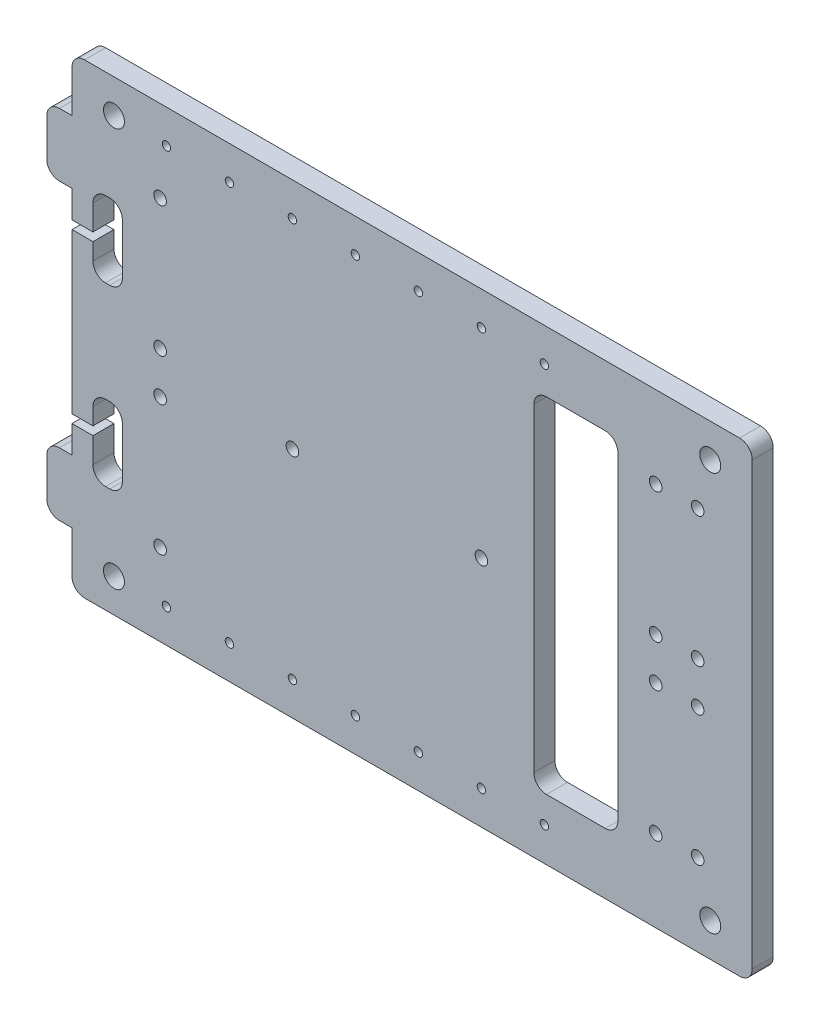
SolidWorks part; units mm, degrees
ref_plane "前视基准面" through (0, 0, 0) normal (0, 0, 1) x (1, 0, 0)
ref_plane "上视基准面" through (0, 0, 0) normal (0, 1, 0) x (1, 0, 0)
ref_plane "右视基准面" through (0, 0, 0) normal (1, 0, 0) x (0, 0, -1)
sketch "草图1" plane through (0, 0, 0) normal (0, 0, 1) x (1, 0, 0)
  line L1 (0, 0) -> (162, 0)
  line L2 (0, 0) -> (0, -111)
  line L3 (0, -111) -> (162, -111)
  line L4 (162, 0) -> (162, -111)
  dimension "D1" = 111
  dimension "D2" = 162
extrude "凸台-拉伸1" add sketch "草图1" along normal blind 5
sketch "草图2" plane through (0, 0, 0) normal (0, 0, -1) x (-1, 0, 0)
  line L8 (-130, -96.5) -> (-130, -14.5)
  line L9 (-130, -14.5) -> (-110, -14.5)
  line L10 (-110, -14.5) -> (-110, -96.5)
  line L11 (-110, -96.5) -> (-130, -96.5)
extrude "切除-拉伸1" cut sketch "草图2" against normal up to next
sketch "草图3" plane through (0, 0, 5) normal (0, 0, 1) x (1, 0, 0)
  line L0 (162, -55.5) -> (0, -55.5) construction
  line L1 (162, -111) -> (162, 0) construction
  line L2 (0, 0) -> (0, -111) construction
  line L3 (162, 0) -> (0, 0) construction
  line L7 (5, -85.5) -> (5, -25.5)
  line L8 (5, -25.5) -> (12, -25.5)
  line L9 (12, -25.5) -> (12, -85.5)
  line L13 (5, -85.5) -> (12, -85.5)
  line L15 (0, 0) -> (0, -111) construction
  circle A0 centre (149, -60.5) radius 1.5
  circle A1 centre (139, -60.5) radius 1.5
  circle A2 centre (149, -91.5) radius 1.5
  circle A3 centre (139, -91.5) radius 1.5
  circle A4 centre (149, -50.5) radius 1.5
  circle A5 centre (139, -50.5) radius 1.5
  circle A20 centre (22.5, -103) radius 1
  circle A27 centre (22.5, -8) radius 1
  circle A34 centre (21, -60.5) radius 1.5
  circle A35 centre (21, -91.5) radius 1.5
  circle A36 centre (21, -50.5) radius 1.5
  circle A37 centre (21, -19.5) radius 1.5
  circle A43 centre (10, -8) radius 2.5
  circle A44 centre (152, -8) radius 2.5
  circle A45 centre (152, -103) radius 2.5
  circle A46 centre (10, -103) radius 2.5
  circle A47 centre (37.5, -103) radius 1
  circle A48 centre (52.5, -103) radius 1
  circle A49 centre (67.5, -103) radius 1
  circle A50 centre (82.5, -103) radius 1
  circle A51 centre (97.5, -103) radius 1
  circle A52 centre (37.5, -8) radius 1
  circle A53 centre (52.5, -8) radius 1
  circle A54 centre (67.5, -8) radius 1
  circle A55 centre (82.5, -8) radius 1
  circle A56 centre (97.5, -8) radius 1
  circle A57 centre (112.5, -8) radius 1
  circle A58 centre (139, -19.5) radius 1.5
  circle A59 centre (149, -19.5) radius 1.5
  circle A60 centre (112.5, -103) radius 1
  circle A61 centre (52.5, -55.5) radius 1.5
  circle A62 centre (97.5, -55.5) radius 1.5
  point P113 (12, -55.5)
  point P114 (5, -55.5)
  dimension "D1" = 3
  dimension "D7" = 22.5
  dimension "D12" = 3
  dimension "D20" = 5
  dimension "D25" = 5
  dimension "D29" = 22.5
  dimension "D5" = 10
  dimension "D6" = 7
  dimension "D8" = 7
  dimension "D2" = 5
  dimension "D3" = 5
  dimension "D4" = 10
  dimension "D21" = 10
  dimension "D22" = 8
  dimension "D23" = 8
  dimension "D26" = 5
  dimension "D27" = 7
  dimension "D28" = 30
extrude "切除-拉伸2" cut sketch "草图3" against normal up to next (5 mm away)
fillet "圆角1" radius 3 12 edges at (162, -111, 2.5) (162, 0, 2.5) (0, 0, 2.5) (0, -111, 2.5) (12, -85.5, 2.5) (5, -85.5, 2.5) (12, -25.5, 2.5) (5, -25.5, 2.5) (110, -96.5, 2.5) (130, -96.5, 2.5) (110, -14.5, 2.5) (130, -14.5, 2.5)
sketch "草图4" plane through (0, 0, 0) normal (-1, 0, 0) x (0, 0, 1)
  line L0 (0, -55.5) -> (5, -55.5) construction
  line L1 (0, -3) -> (0, -108) construction
  line L2 (5, -82.5) -> (5, -28.5) construction
  circle A0 centre (2.5, -35.5) radius 1
  circle A1 centre (2.5, -75.5) radius 1
  dimension "D2" = 2
  dimension "D1" = 20
  dimension "D3" = 2.5
extrude "切除-拉伸3" [suppressed] cut sketch "草图4" against normal up to next
sketch "Sketch1" plane through (0, 0, 0) normal (-1, 0, 0) x (0, 0, 1)
  line L0 (0, -55.5) -> (5, -55.5) construction
  line L1 (0, -3) -> (0, -108) construction
  line L2 (5, -3) -> (5, -108) construction
  line L3 (2.5, -55.5) -> (2.5, -20.5) construction
  line L4 (0, -83) -> (5, -83)
  line L5 (0, -13) -> (5, -13)
  line L6 (0, -13) -> (0, -28)
  line L7 (0, -28) -> (5, -28)
  line L8 (5, -13) -> (5, -28)
  line L9 (0, -13) -> (5, -28) construction
  line L10 (0, -28) -> (5, -13) construction
  line L11 (5, -98) -> (5, -83)
  line L12 (0, -98) -> (0, -83)
  line L13 (0, -98) -> (5, -98)
  dimension "D1" = 15
  dimension "D2" = 35
extrude "Boss-Extrude1" add sketch "Sketch1" along normal blind 6
sketch "Sketch2" plane through (0, 0, 0) normal (0, 0, 1) x (1, 0, 0)
  line L0 (0, -67.5) -> (0, -43.5)
  line L1 (0, -28) -> (0, -83) construction
  line L2 (0, -43.5) -> (12, -43.5)
  line L3 (12, -82.5) -> (12, -28.5) construction
  line L4 (12, -43.5) -> (12, -67.5)
  line L5 (0, -55.5) -> (12, -55.5) construction
  line L6 (0, -67.5) -> (12, -67.5)
  dimension "D1" = 24
extrude "Boss-Extrude2" add sketch "Sketch2" along normal blind 5
sketch "Sketch3" plane through (0, 0, 0) normal (0, 0, 1) x (1, 0, 0)
  line L0 (0, -55.5) -> (5, -55.5) construction
  line L1 (0, -28) -> (0, -83) construction
  line L2 (5, -43.5) -> (5, -67.5) construction
  line L3 (2.5, -55.5) -> (2.5, -35.5) construction
  line L4 (5, -28.5) -> (5, -43.5) construction
  line L5 (0, -36.5) -> (5, -36.5)
  line L6 (0, -36.5) -> (0, -34.5)
  line L7 (0, -34.5) -> (5, -34.5)
  line L8 (5, -36.5) -> (5, -34.5)
  line L9 (0, -36.5) -> (5, -34.5) construction
  line L10 (0, -34.5) -> (5, -36.5) construction
  line L11 (5, -74.5) -> (5, -76.5)
  line L12 (0, -74.5) -> (5, -74.5)
  line L13 (0, -74.5) -> (0, -76.5)
  line L14 (0, -76.5) -> (5, -76.5)
  dimension "D1" = 2
  dimension "D2" = 20
extrude "Cut-Extrude2" cut sketch "Sketch3" along normal through all
fillet "Fillet1" radius 3 8 edges at (12, -67.5, 2.5) (5, -67.5, 2.5) (12, -43.5, 2.5) (5, -43.5, 2.5) (-6, -98, 2.5) (-6, -83, 2.5) (-6, -28, 2.5) (-6, -13, 2.5)
